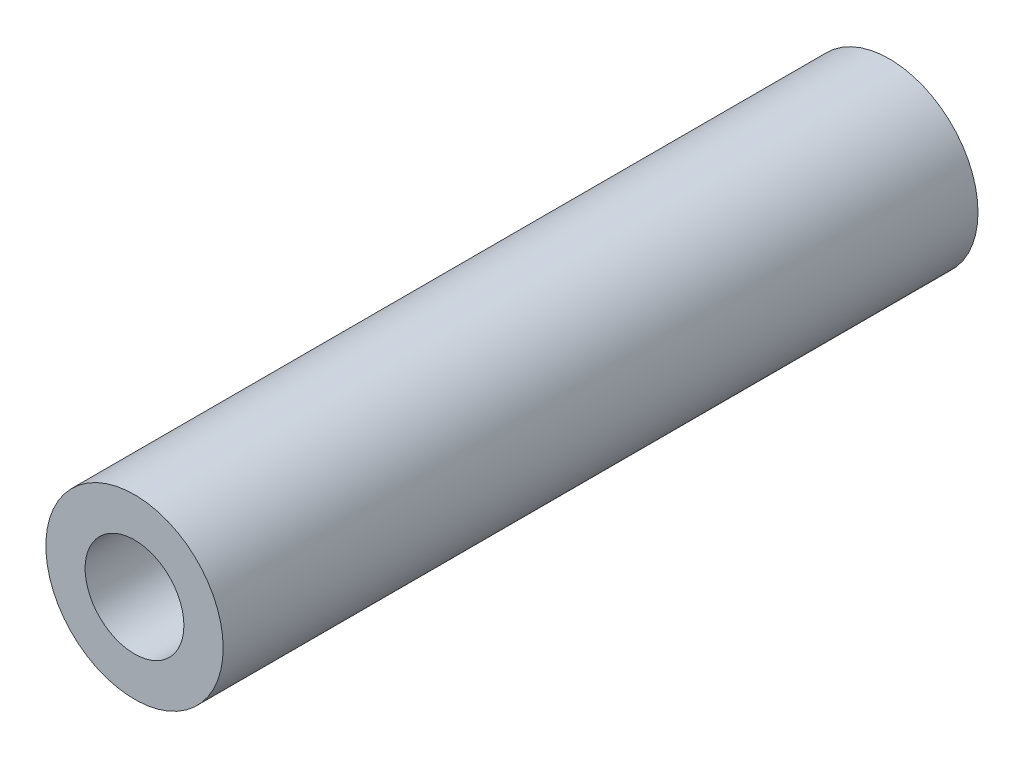
SolidWorks part; units mm, degrees
ref_plane "Alzado" through (0, 0, 0) normal (0, 0, 1) x (1, 0, 0)
ref_plane "Planta" through (0, 0, 0) normal (0, 1, 0) x (1, 0, 0)
ref_plane "Vista lateral" through (0, 0, 0) normal (1, 0, 0) x (0, 0, -1)
sketch "Croquis1" plane through (0, 0, 0) normal (0, 0, 1) x (1, 0, 0)
  circle A0 centre (0, 0) radius 9.75
  circle A1 centre (0, 0) radius 17.5
  dimension "D1" = 19.5
  dimension "D2" = 35
extrude "Saliente-Extruir1" add sketch "Croquis1" along normal blind 149
